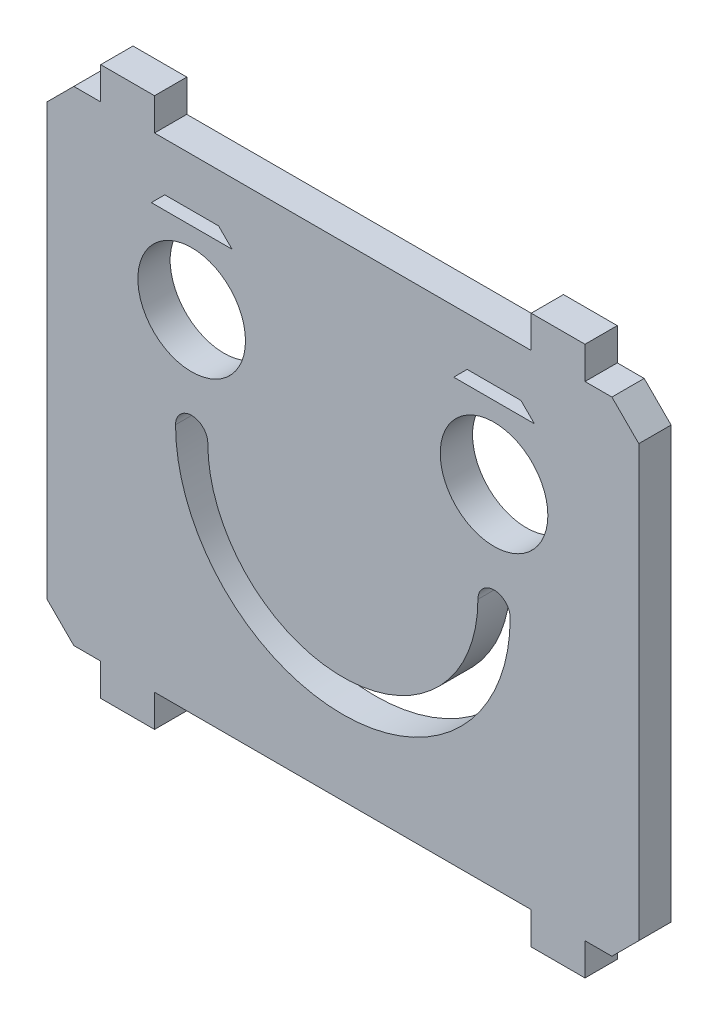
SolidWorks part; units mm, degrees
ref_plane "Front Plane" through (0, 0, 0) normal (0, 0, 1) x (1, 0, 0)
ref_plane "Top Plane" through (0, 0, 0) normal (0, 1, 0) x (1, 0, 0)
ref_plane "Right Plane" through (0, 0, 0) normal (1, 0, 0) x (0, 0, -1)
sketch "Sketch1" plane through (0, 0, 0) normal (0, 0, 1) x (1, 0, 0)
  line L0 (0, 0) -> (0, 48) construction
  line L1 (0, 48) -> (-40, 48) construction
  line L2 (-45, 51) -> (-45, 45)
  line L3 (-45, 45) -> (-35, 45)
  line L4 (-45, 51) -> (-35, 51)
  line L5 (-35, 51) -> (-35, 45)
  line L6 (0, 0) -> (-56.1937, 0) construction
  line L7 (45, 51) -> (35, 51)
  line L8 (45, 51) -> (45, 45)
  line L9 (45, 45) -> (35, 45)
  line L10 (35, 51) -> (35, 45)
  line L11 (45, -51) -> (45, -45)
  line L12 (45, -45) -> (35, -45)
  line L13 (35, -51) -> (35, -45)
  line L14 (45, -51) -> (35, -51)
  line L15 (-45, -51) -> (-35, -51)
  line L16 (-45, -51) -> (-45, -45)
  line L17 (-45, -45) -> (-35, -45)
  line L18 (-35, -51) -> (-35, -45)
  line L19 (0, 0) -> (55, 0) construction
  line L20 (55, -40) -> (55, 40)
  line L21 (50, 45) -> (-50, 45)
  line L22 (-55, 40) -> (-55, -40)
  line L23 (-50, -45) -> (50, -45)
  line L24 (-50, 45) -> (-55, 40)
  line L25 (55, 40) -> (50, 45)
  line L26 (50, -45) -> (55, -40)
  line L27 (-55, -40) -> (-50, -45)
  line L28 (0, 0) -> (-28.0968, 0) construction
  line L29 (-28.0968, 0) -> (-28.0968, 20) construction
  line L30 (28.0968, 0) -> (28.0968, 20) construction
  line L31 (-28.0968, 30) -> (-28.0968, 38) construction
  line L34 (-33.0968, 36) -> (-23.0968, 36)
  line L36 (-23.0968, 36) -> (-20.5968, 33.5)
  line L37 (-35.5968, 33.5) -> (-33.0968, 36)
  line L38 (33.0968, 36) -> (23.0968, 36)
  line L39 (23.0968, 36) -> (20.5968, 33.5)
  line L42 (35.5968, 33.5) -> (33.0968, 36)
  line L44 (20.5968, 33.5) -> (35.5968, 33.5)
  line L45 (-20.5968, 33.5) -> (-35.5968, 33.5)
  arc A0 (28.0968, 0) -> (-28.0968, 0) centre (0, 0) cw construction
  arc A1 (-31.0968, 0) -> (31.0968, 0) centre (0, 0) ccw
  arc A2 (-25.0968, 0) -> (25.0968, 0) centre (0, 0) ccw
  arc A3 (-25.0968, 0) -> (-31.0968, 0) centre (-28.0968, 0) ccw
  arc A4 (31.0968, 0) -> (25.0968, 0) centre (28.0968, 0) ccw
  circle A5 centre (-28.0968, 20) radius 10
  circle A6 centre (28.0968, 20) radius 10
  point P7 (-40, 48)
  point P23 (55, -45)
  point P24 (55, 45)
  point P25 (-55, 45)
  point P26 (-55, -45)
  point P40 (0, -28.0968)
  point P52 (-28.0968, 38)
  point P54 (-35.5968, 36)
  point P55 (-20.5968, 36)
  dimension "D5" = 20
  dimension "D6" = 3
  dimension "D7" = 20
  dimension "D12" = 20
  dimension "D13" = 8
  dimension "D1" = 48
  dimension "D2" = 40
  dimension "D3" = 55
  dimension "D4" = 110
extrude "Boss-Extrude2" add sketch "Sketch1" along normal blind 6
